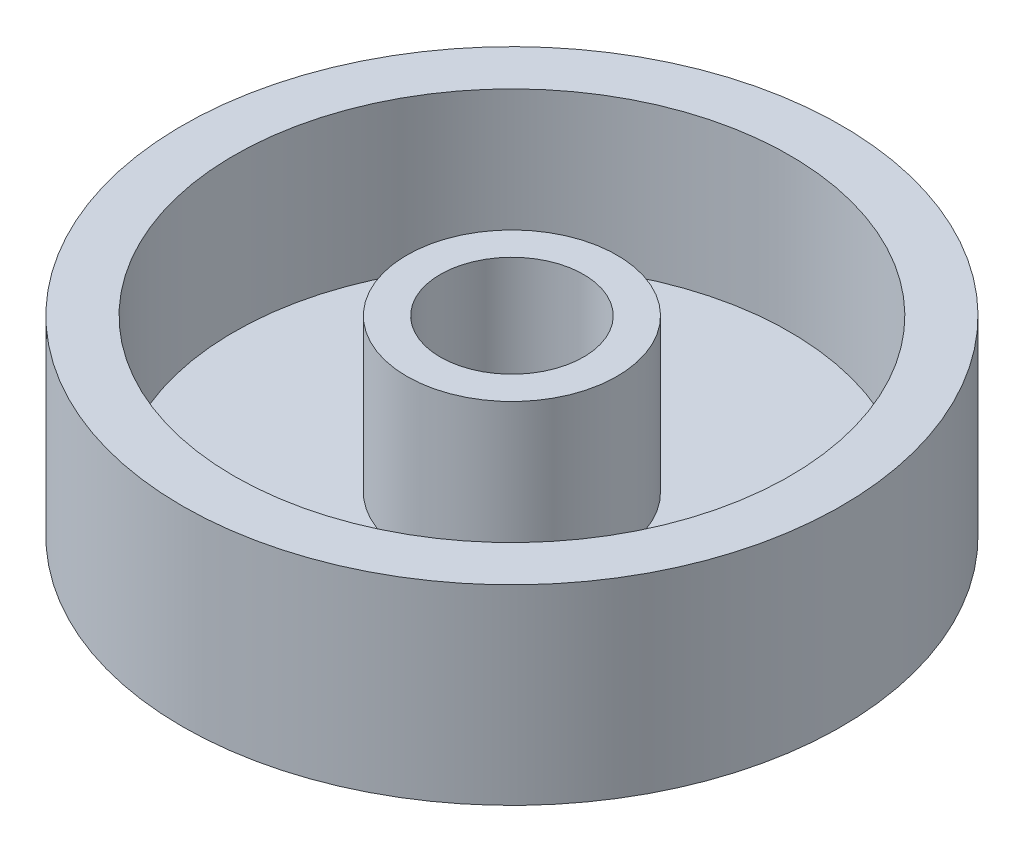
SolidWorks part; units mm, degrees
material "Автоматная латунь, UNS C36000"
ref_plane "Спереди" through (0, 0, 0) normal (0, 0, 1) x (1, 0, 0)
ref_plane "Сверху" through (0, 0, 0) normal (0, 1, 0) x (1, 0, 0)
ref_plane "Справа" through (0, 0, 0) normal (1, 0, 0) x (0, 0, -1)
sketch "Эскиз1" plane through (0, 0, 0) normal (0, 1, 0) x (1, 0, 0)
  circle A0 centre (0, 0) radius 6.9
extrude "Вытянуть1" add sketch "Эскиз1" along normal blind 4
sketch "Эскиз2" plane through (0, 4, 0) normal (0, 1, 0) x (1, 0, 0)
  circle A0 centre (0, 0) radius 5.8171
  circle A1 centre (0, 0) radius 2.2
extrude "Вытянуть2" cut sketch "Эскиз2" against normal blind 3.2
sketch "Эскиз3" plane through (0, 4, 0) normal (0, 1, 0) x (1, 0, 0)
  circle A0 centre (0, 0) radius 1.5
extrude "Вытянуть3" cut sketch "Эскиз3" against normal through all
